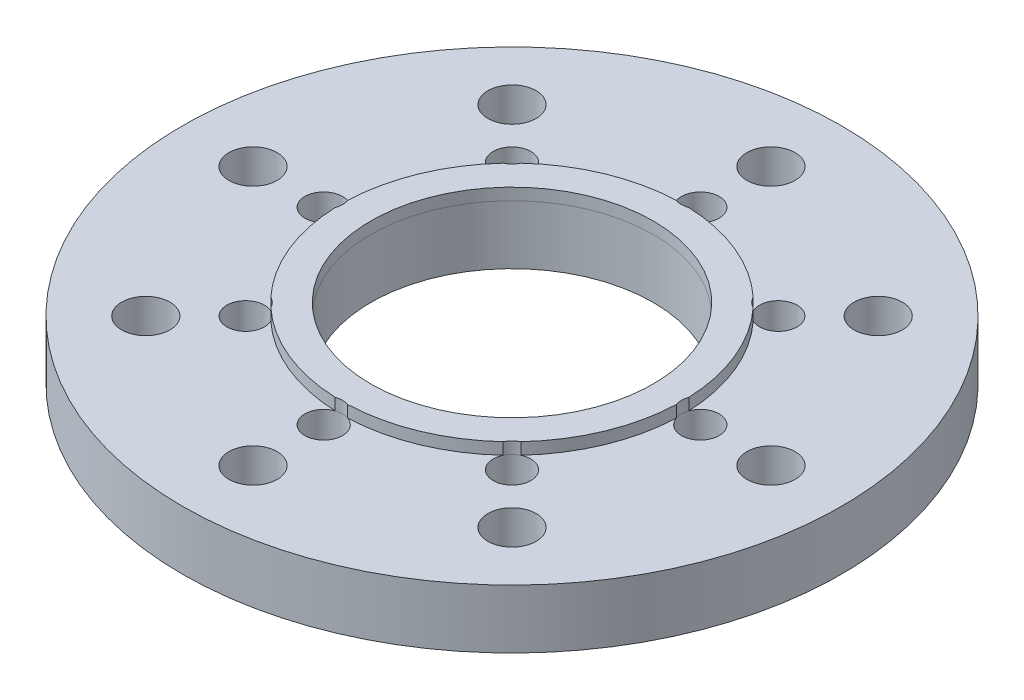
SolidWorks part; units mm, degrees
material "6063-O"
ref_plane "Front Plane" through (0, 0, 0) normal (0, 0, 1) x (1, 0, 0)
ref_plane "Top Plane" through (0, 0, 0) normal (0, 1, 0) x (1, 0, 0)
ref_plane "Right Plane" through (0, 0, 0) normal (1, 0, 0) x (0, 0, -1)
sketch "Sketch1" plane through (0, 0, 0) normal (0, 1, 0) x (1, 0, 0)
  circle A0 centre (0, 0) radius 14
  circle A1 centre (0, 0) radius 6
  dimension "D1" = 28
  dimension "D2" = 12
extrude "Boss-Extrude1" add sketch "Sketch1" along normal blind 2.5
sketch "Sketch2" plane through (0, 2.5, 0) normal (0, 1, 0) x (1, 0, 0)
  circle A0 centre (0, 0) radius 8 construction
  dimension "D1" = 16
sketch "Sketch5" plane through (0, 2.5, 0) normal (0, 1, 0) x (1, 0, 0)
  circle A0 centre (0, 0) radius 6
  circle A1 centre (0, 0) radius 7.25
  dimension "D1" = 12
  dimension "D2" = 14.5
extrude "Boss-Extrude2" add sketch "Sketch5" along normal blind 0.5 separate body
sketch "Sketch8" plane through (0, 0, 0) normal (0, -1, 0) x (-1, 0, 0)
  circle A0 centre (0, 0) radius 11 construction
  dimension "D1" = 22
hole_wizard "M2.5 Tapped Hole1" positions "Sketch9" profile "Sketch10" tap size "M2.5" standard "ISO" end condition through all
sketch "Sketch9" plane through (0, 0, 0) normal (0, -1, 0) x (-1, 0, 0)
  circle A0 centre (0, 0) radius 11 construction
  point P0 (0, -11)
sketch "Sketch10" plane through (0, 0, 11) normal (1, 0, 0) x (0, 0, -1)
  line L0 (0, 0) -> (0, 2.5)
  line L1 (0, 2.5) -> (1.025, 2.5)
  line L2 (1.025, 2.5) -> (1.025, 0)
  line L5 (1.025, 0) -> (0, 0)
  line L11 (0, -6.35) -> (0, 107.95) construction
  dimension "Thru Tap Drill Dia." = 2.05
  dimension "Thru Tap Drill Depth" = 2.5
cosmetic thread "Hole Thread2" parameters "D2"=2.5
pattern_circular "CirPattern3" count 8 over 360 about axis through (0, 0, 0) along (0, 1, 0) of "M2.5 Tapped Hole1"
cosmetic thread "Cosmetic Thread8" parameters "D2"=2.5
cosmetic thread "Cosmetic Thread9" parameters "D2"=2.5
cosmetic thread "Cosmetic Thread10" parameters "D2"=2.5
cosmetic thread "Cosmetic Thread11" parameters "D2"=2.5
cosmetic thread "Cosmetic Thread12" parameters "D2"=2.5
cosmetic thread "Cosmetic Thread13" parameters "D2"=2.5
cosmetic thread "Cosmetic Thread14" parameters "D2"=2.5
sketch "Sketch18" plane through (0, 3, 0) normal (0, 1, 0) x (1, 0, 0)
  circle A0 centre (0, 0) radius 8 construction
  dimension "D1" = 16
hole_wizard "M2 Tapped Hole1" positions "Sketch19" profile "Sketch20" tap size "M2" standard "ISO" end condition through all
sketch "Sketch19" plane through (0, 3, 0) normal (0, 1, 0) x (1, 0, 0)
  circle A0 centre (0, 0) radius 8 construction
  point P0 (0, 8)
sketch "Sketch20" plane through (0, 3, -8) normal (1, 0, 0) x (0, 0, 1)
  line L0 (0, 0) -> (0, 3)
  line L1 (0, 3) -> (0.8, 3)
  line L2 (0.8, 3) -> (0.8, 0)
  line L5 (0.8, 0) -> (0, 0)
  line L11 (0, -6.35) -> (0, 107.95) construction
  dimension "Thru Tap Drill Dia." = 1.6
  dimension "Thru Tap Drill Depth" = 3
cosmetic thread "Hole Thread3" parameters "D2"=2
pattern_circular "CirPattern4" count 8 over 360 about axis through (0, 0, 0) along (0, 1, 0) of "M2 Tapped Hole1"
cosmetic thread "Cosmetic Thread1" parameters "D2"=2.5
cosmetic thread "Cosmetic Thread2" parameters "D2"=2.5
cosmetic thread "Cosmetic Thread3" parameters "D2"=2.5
cosmetic thread "Cosmetic Thread4" parameters "D2"=2.5
cosmetic thread "Cosmetic Thread6" parameters "D2"=2.5
cosmetic thread "Cosmetic Thread7" parameters "D2"=2.5
